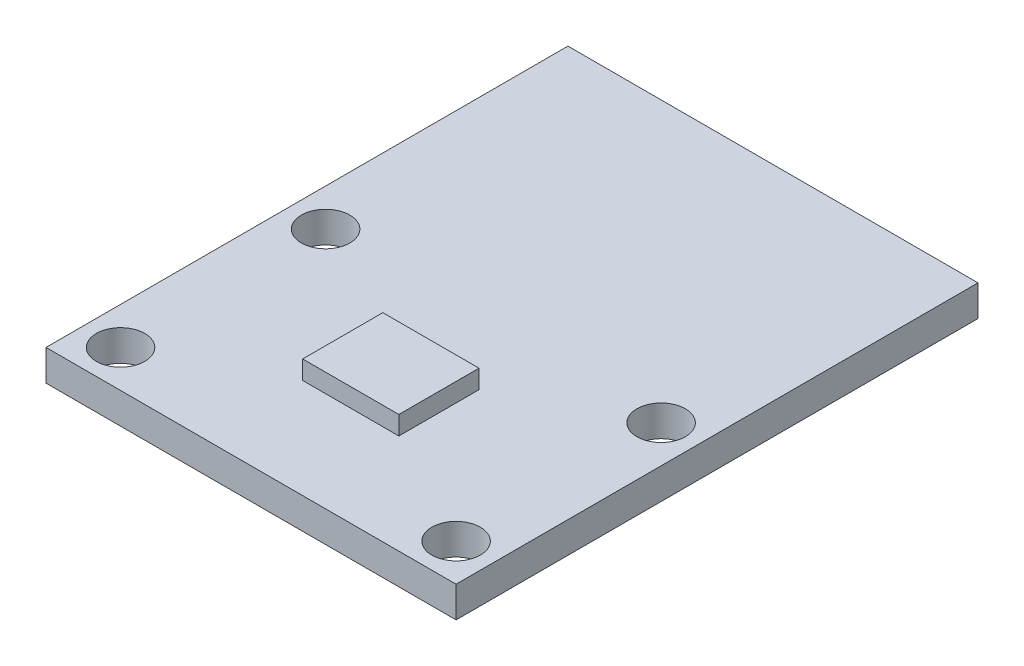
SolidWorks part; units mm, degrees
ref_plane "Front Plane" through (0, 0, 0) normal (0, 0, 1) x (1, 0, 0)
ref_plane "Top Plane" through (0, 0, 0) normal (0, 1, 0) x (1, 0, 0)
ref_plane "Right Plane" through (0, 0, 0) normal (1, 0, 0) x (0, 0, -1)
sketch "Sketch1" plane through (0, 0, 0) normal (0, 1, 0) x (1, 0, 0)
  line L0 (0, 14) -> (0, -14) construction
  line L1 (-11, 14) -> (11, 14)
  line L2 (-11, 14) -> (-11, -14)
  line L3 (-11, -14) -> (11, -14)
  line L4 (11, 14) -> (11, -14)
  line L5 (-11, 14) -> (11, -14) construction
  line L6 (-11, -14) -> (11, 14) construction
  line L7 (9, -6.5) -> (11, -6.5) construction
  line L8 (-9, -1) -> (9, -1) construction
  line L9 (-9, -1) -> (-9, -12) construction
  line L10 (-9, -12) -> (9, -12) construction
  line L11 (9, -1) -> (9, -12) construction
  line L12 (0, -12) -> (0, -14) construction
  line L13 (-9, -6.5) -> (9, -6.5) construction
  circle A0 centre (-9, -1) radius 1.3
  circle A1 centre (9, -1) radius 1.3
  circle A2 centre (-9, -12) radius 1.3
  circle A3 centre (9, -12) radius 1.3
  point P0 (0, 0)
  point P12 (0, -1)
  point P17 (0, -6.5)
  dimension "D5" = 2.6
  dimension "D1" = 22
  dimension "D2" = 28
  dimension "D3" = 11
  dimension "D4" = 18
extrude "Boss-Extrude1" add sketch "Sketch1" along normal mid plane 1.66
sketch "Sketch2" plane through (0, 0.83, 0) normal (0, 1, 0) x (1, 0, 0)
  line L1 (-2.58, -4.35) -> (2.58, -4.35)
  line L2 (-2.58, -4.35) -> (-2.58, -8.65)
  line L3 (-2.58, -8.65) -> (2.58, -8.65)
  line L4 (2.58, -4.35) -> (2.58, -8.65)
  line L5 (-2.58, -4.35) -> (2.58, -8.65) construction
  line L6 (-2.58, -8.65) -> (2.58, -4.35) construction
  point P0 (0, -6.5)
  dimension "D1" = 5.16
  dimension "D2" = 4.3
extrude "Boss-Extrude2" add sketch "Sketch2" along normal blind 1
sketch "Sketch3" plane through (0, 0, 0) normal (0, 1, 0) x (1, 0, 0)
  line L0 (0, 14) -> (0, -14) construction
  line L1 (0, 14) -> (0, -14) construction
  line L2 (11, 14) -> (-11, 14) construction
  line L3 (-10, 12.3) -> (10, 12.3)
  line L4 (-10, 12.3) -> (-10, 7.3)
  line L5 (-10, 7.3) -> (10, 7.3)
  line L6 (10, 12.3) -> (10, 7.3)
  line L7 (-10, 12.3) -> (10, 7.3) construction
  line L8 (-10, 7.3) -> (10, 12.3) construction
  line L9 (11, -14) -> (11, 14) construction
  line L10 (-2.3, 5) -> (5, 5)
  line L11 (-2.3, 5) -> (-2.3, 2.5)
  line L12 (-2.3, 2.5) -> (5, 2.5)
  line L13 (5, 5) -> (5, 2.5)
  point P2 (0, 9.8)
  dimension "D1" = 20
  dimension "D2" = 5
  dimension "D3" = 1.7
  dimension "D4" = 7.3
  dimension "D5" = 2.5
  dimension "D6" = 6
  dimension "D7" = 9
ref_plane "Plane1" through (0, 0, 6.5) normal (0, 0, -1) x (-1, 0, 0)
sketch "Sketch4" plane through (0, 0, 6.5) normal (0, 0, -1) x (-1, 0, 0)
  line L0 (0, 4.6251) -> (0, -4.5161) construction
